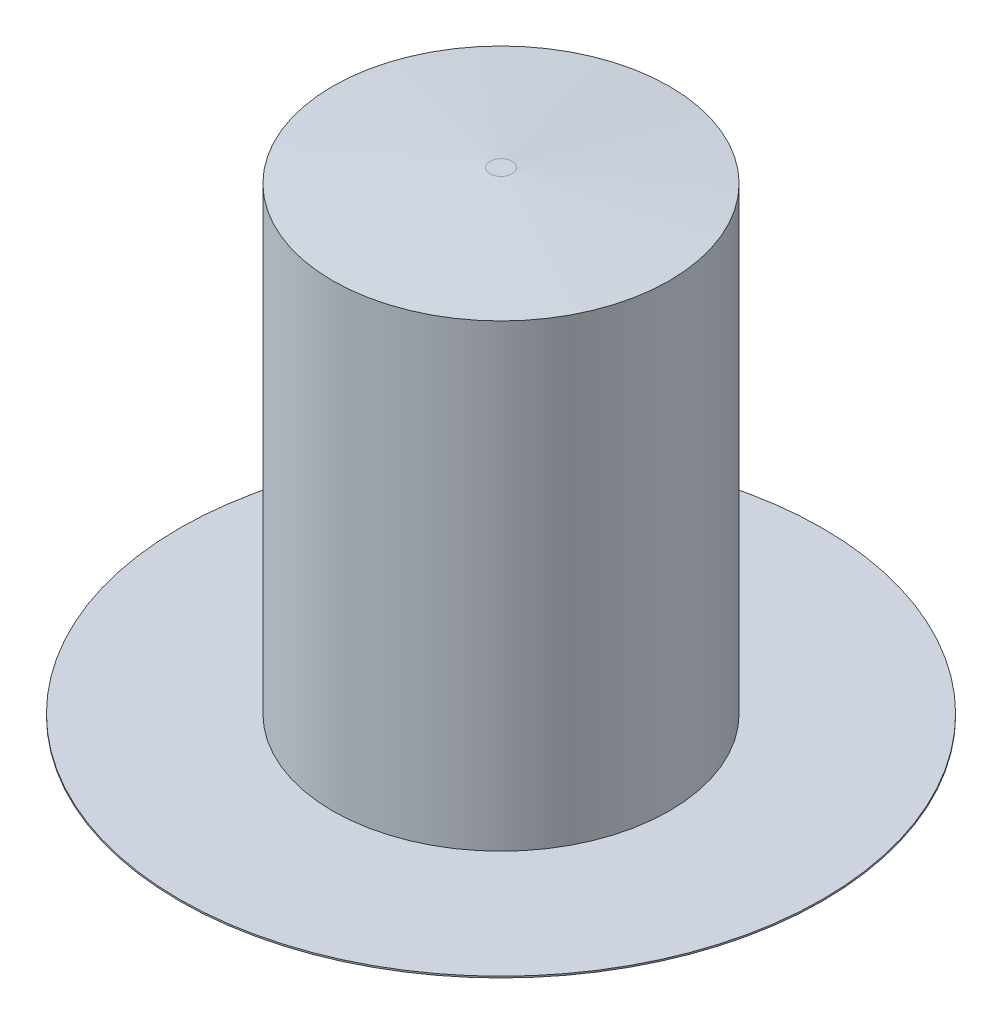
SolidWorks part; units mm, degrees
material "Cast Alloy Steel"
ref_plane "Front Plane" through (0, 0, 0) normal (0, 0, 1) x (1, 0, 0)
ref_plane "Top Plane" through (0, 0, 0) normal (0, 1, 0) x (1, 0, 0)
ref_plane "Right Plane" through (0, 0, 0) normal (1, 0, 0) x (0, 0, -1)
sketch "Sketch1" plane through (0, 0, 0) normal (0, 1, 0) x (1, 0, 0)
  circle A0 centre (0, 0) radius 5.334
  dimension "D1" = 10.668
extrude "Boss-Extrude2" add sketch "Sketch1" along normal blind 0.0254
sketch "Sketch2" plane through (0, 0.0254, 0) normal (0, 1, 0) x (1, 0, 0)
  circle A0 centre (0, 0) radius 5.334
  circle A1 centre (0, 0) radius 2.794
  dimension "D1" = 10.668
extrude "Boss-Extrude4" add sketch "Sketch2" along normal blind 7.62 contours A1
sketch "Sketch3" plane through (0, 7.6454, 0) normal (0, 1, 0) x (1, 0, 0)
  circle A0 centre (0, 0) radius 2.794
extrude "Boss-Extrude5" add sketch "Sketch3" along normal blind 0.2286 draft 85
